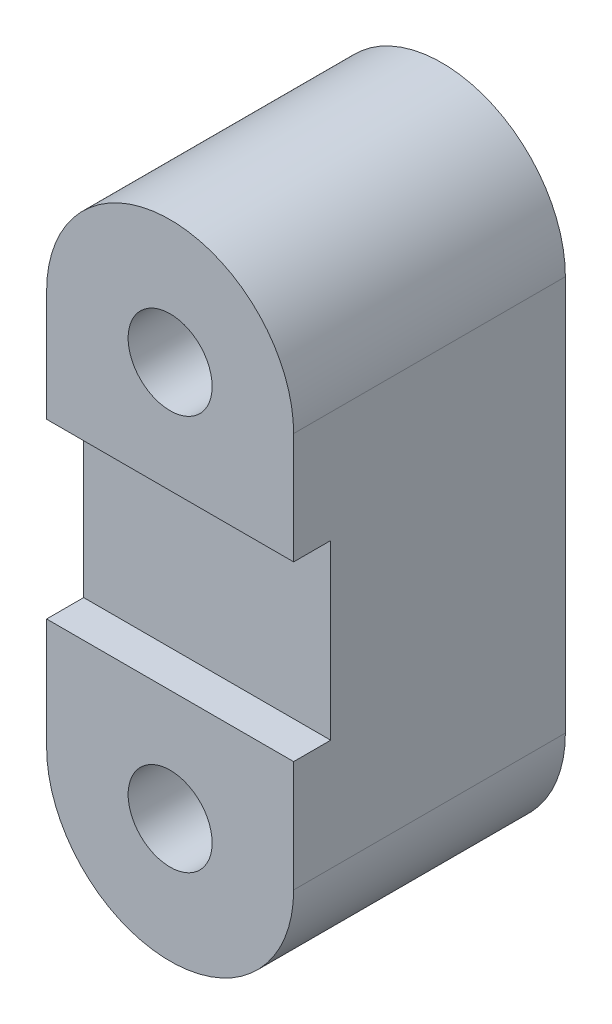
SolidWorks part; units mm, degrees
ref_plane "Front Plane" through (0, 0, 0) normal (0, 0, 1) x (1, 0, 0)
ref_plane "Top Plane" through (0, 0, 0) normal (0, 1, 0) x (1, 0, 0)
ref_plane "Right Plane" through (0, 0, 0) normal (1, 0, 0) x (0, 0, -1)
sketch "Sketch1" plane through (0, 0, 0) normal (0, 0, 1) x (1, 0, 0)
  line L0 (0, -8) -> (0, 8) construction
  line L1 (0, -8) -> (0, 8) construction
  line L2 (-5, -8) -> (-5, 8)
  line L3 (5, -8) -> (5, 8)
  circle A0 centre (0, 8) radius 1.7
  circle A1 centre (0, -8) radius 1.7
  arc A2 (-5, -8) -> (5, -8) centre (0, -8) ccw
  arc A3 (5, 8) -> (-5, 8) centre (0, 8) ccw
  point P4 (0, 0)
  dimension "D1" = 3.4
  dimension "D2" = 5
  dimension "D3" = 16
extrude "Boss-Extrude1" add sketch "Sketch1" along normal blind 11
sketch "Sketch2" plane through (0, 0, 11) normal (0, 0, 1) x (1, 0, 0)
  line L0 (-5, 8) -> (-5, -8) construction
  line L1 (5, -8) -> (5, 8) construction
  line L2 (-5, -3.5) -> (5, -3.5)
  line L3 (-5, -3.5) -> (-5, 3.5)
  line L4 (-5, 3.5) -> (5, 3.5)
  line L5 (5, -3.5) -> (5, 3.5)
  line L6 (0, 0) -> (-5, 0) construction
  dimension "D1" = 7
extrude "Cut-Extrude1" cut sketch "Sketch2" against normal blind 1.5
